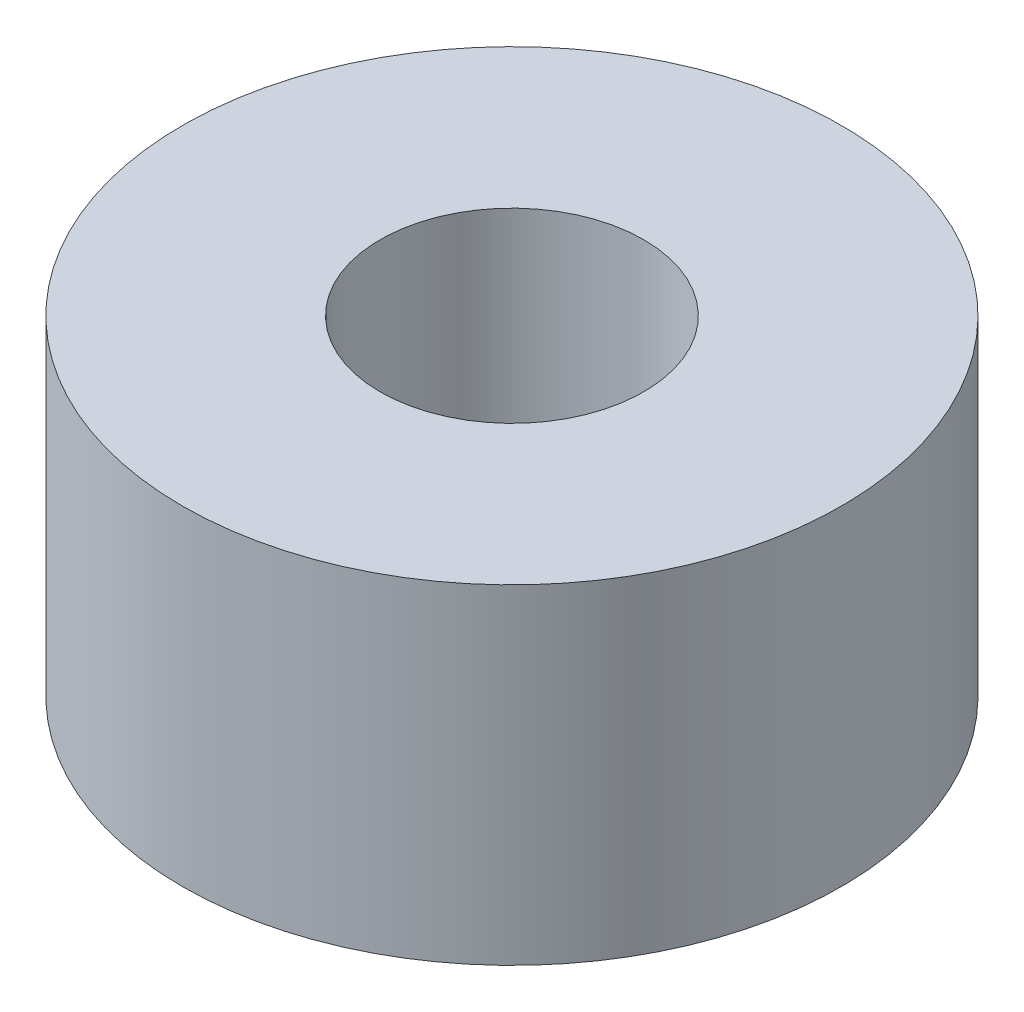
SolidWorks part; units mm, degrees
material "轴承钢"
ref_plane "前视基准面" through (0, 0, 0) normal (0, 0, 1) x (1, 0, 0)
ref_plane "上视基准面" through (0, 0, 0) normal (0, 1, 0) x (1, 0, 0)
ref_plane "右视基准面" through (0, 0, 0) normal (1, 0, 0) x (0, 0, -1)
sketch "草图1" plane through (0, 0, 0) normal (0, 1, 0) x (1, 0, 0)
  circle A0 centre (0, 0) radius 2.5
  circle A1 centre (0, 0) radius 1
  dimension "D1" = 2
  dimension "D2" = 5
extrude "凸台-拉伸1" add sketch "草图1" along normal blind 2.5
